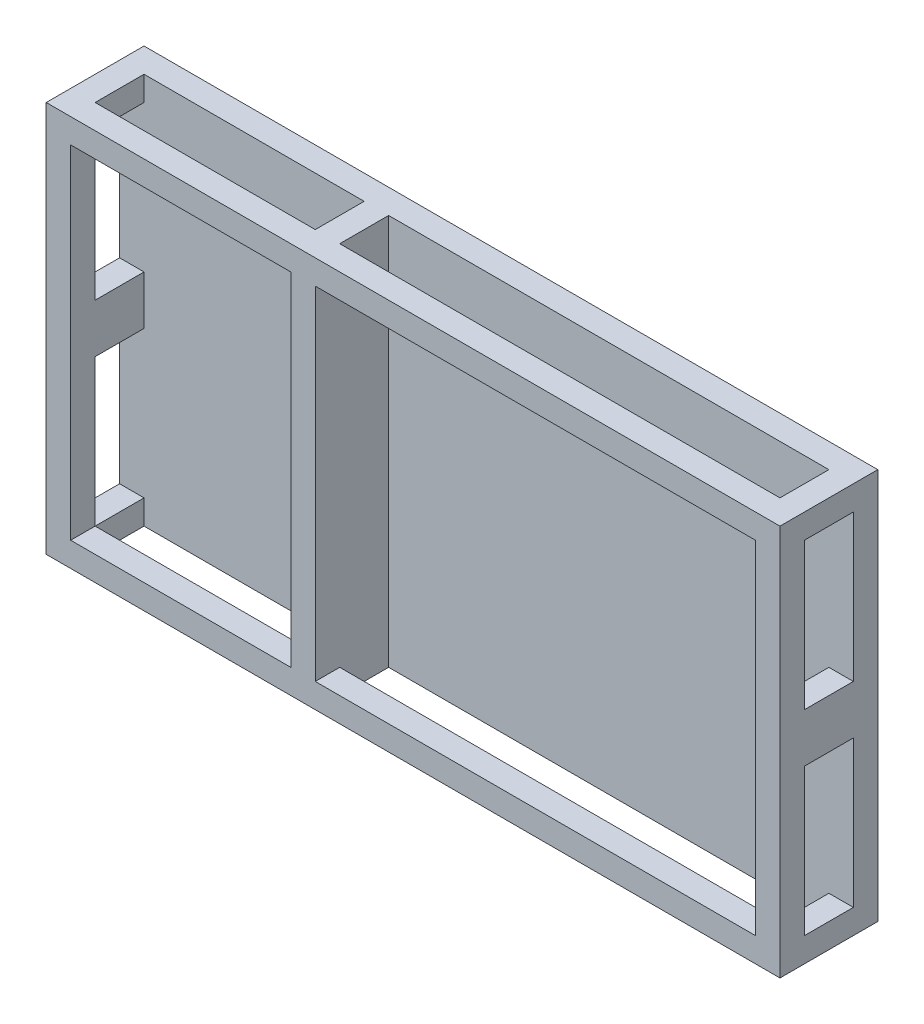
SolidWorks part; units mm, degrees
ref_plane "Plano frontal" through (0, 0, 0) normal (0, 0, 1) x (1, 0, 0)
ref_plane "Plano superior" through (0, 0, 0) normal (0, 1, 0) x (1, 0, 0)
ref_plane "Plano direito" through (0, 0, 0) normal (1, 0, 0) x (0, 0, -1)
sketch "Esboço1" plane through (0, 0, 0) normal (0, 0, 1) x (1, 0, 0)
  line L1 (0, 0) -> (150, 0)
  line L2 (0, 0) -> (0, 80)
  line L3 (0, 80) -> (150, 80)
  line L4 (150, 0) -> (150, 80)
  dimension "D1" = 150
  dimension "D2" = 80
extrude "Ressalto-extrusão1" add sketch "Esboço1" along normal blind 20
sketch "Esboço2" plane through (0, 80, 0) normal (0, 1, 0) x (1, 0, 0)
  line L0 (150, 0) -> (0, 0) construction
  line L1 (5, -5) -> (145, -5)
  line L2 (5, -5) -> (5, -15)
  line L3 (5, -15) -> (145, -15)
  line L4 (145, -5) -> (145, -15)
  line L5 (0, -20) -> (0, 0) construction
  dimension "D1" = 10
  dimension "D2" = 140
  dimension "D3" = 5
  dimension "D4" = 5
extrude "Corte-extrusão1" cut sketch "Esboço2" against normal through all
sketch "Esboço3" plane through (0, 0, 0) normal (-1, 0, 0) x (0, 0, 1)
  line L0 (20, 80) -> (0, 80) construction
  line L1 (5, 75) -> (15, 75)
  line L2 (5, 75) -> (5, 5)
  line L3 (5, 5) -> (15, 5)
  line L4 (15, 75) -> (15, 5)
  line L5 (20, 80) -> (20, 0) construction
  dimension "D1" = 10
  dimension "D2" = 70
  dimension "D3" = 5
  dimension "D4" = 5
extrude "Corte-extrusão2" cut sketch "Esboço3" against normal through all
sketch "Esboço4" plane through (0, 0, 20) normal (0, 0, 1) x (1, 0, 0)
  line L0 (150, 80) -> (0, 80) construction
  line L1 (5, 75) -> (50, 75)
  line L2 (5, 75) -> (5, 5)
  line L3 (5, 5) -> (50, 5)
  line L4 (50, 75) -> (50, 5)
  line L5 (0, 80) -> (0, 0) construction
  line L6 (150, 0) -> (150, 80) construction
  line L7 (55, 75) -> (145, 75)
  line L8 (55, 75) -> (55, 5)
  line L9 (55, 5) -> (145, 5)
  line L10 (145, 75) -> (145, 5)
  line L11 (0, 0) -> (150, 0) construction
  dimension "D1" = 70
  dimension "D2" = 45
  dimension "D3" = 5
  dimension "D4" = 5
  dimension "D5" = 5
  dimension "D6" = 5
  dimension "D7" = 5
  dimension "D8" = 5
extrude "Corte-extrusão3" cut sketch "Esboço4" against normal up to surface (15 mm away) up to face at (75, 40, 5)
sketch "Esboço5" plane through (0, 80, 0) normal (0, 1, 0) x (1, 0, 0)
  line L0 (150, -20) -> (0, -20) construction
  line L1 (50, -20) -> (55.0021, -20)
  line L2 (50, -20) -> (50, 0)
  line L3 (50, 0) -> (55.0021, 0)
  line L4 (55.0021, -20) -> (55.0021, 0)
  line L5 (150, 0) -> (0, 0) construction
  line L6 (50, -15) -> (50, -20) construction
  point P10 (0, 0)
  dimension "D1" = 5.0021
extrude "Ressalto-extrusão2" add sketch "Esboço5" against normal blind 80
sketch "Esboço6" plane through (0, 0, 0) normal (-1, 0, 0) x (0, 0, 1)
  line L0 (0, 80) -> (0, 0) construction
  line L1 (0, 45) -> (20, 45)
  line L2 (0, 45) -> (0, 35)
  line L3 (0, 35) -> (20, 35)
  line L4 (20, 45) -> (20, 35)
  line L5 (20, 80) -> (20, 0) construction
  line L6 (20, 80) -> (0, 80) construction
  line L7 (20, 0) -> (0, 0) construction
  dimension "D1" = 35
  dimension "D2" = 35
extrude "Ressalto-extrusão3" add sketch "Esboço6" against normal blind 5
sketch "Esboço7" plane through (150, 0, 0) normal (1, 0, 0) x (0, 0, -1)
  line L0 (-20, 0) -> (-20, 80) construction
  line L1 (-20, 45) -> (0, 45)
  line L2 (-20, 45) -> (-20, 35)
  line L3 (-20, 35) -> (0, 35)
  line L4 (0, 45) -> (0, 35)
  line L6 (-20, 80) -> (0, 80) construction
  line L8 (-20, 0) -> (0, 0) construction
  line L9 (0, 0) -> (0, 80) construction
  dimension "D1" = 35
  dimension "D2" = 35
extrude "Ressalto-extrusão4" add sketch "Esboço7" against normal blind 5
sketch "Esboço8" plane through (0, 80, 0) normal (0, 1, 0) x (1, 0, 0)
  line L0 (60.0021, -10) -> (140.0021, -10) construction
  line L1 (60.0021, -6.5) -> (140.0021, -6.5)
  line L2 (60.0021, -13.5) -> (140.0021, -13.5)
  line L4 (55.0021, -5) -> (145, -5)
  line L5 (55.0021, -5) -> (55.0021, -15)
  line L6 (55.0021, -15) -> (145, -15)
  line L7 (145, -5) -> (145, -15)
  arc A0 (60.0021, -6.5) -> (60.0021, -13.5) centre (60.0021, -10) ccw
  arc A1 (140.0021, -13.5) -> (140.0021, -6.5) centre (140.0021, -10) ccw
  point P2 (100.0021, -10)
  dimension "D2" = 5
  dimension "D1" = 80
  dimension "D3" = 7
  dimension "D4" = 1.5
